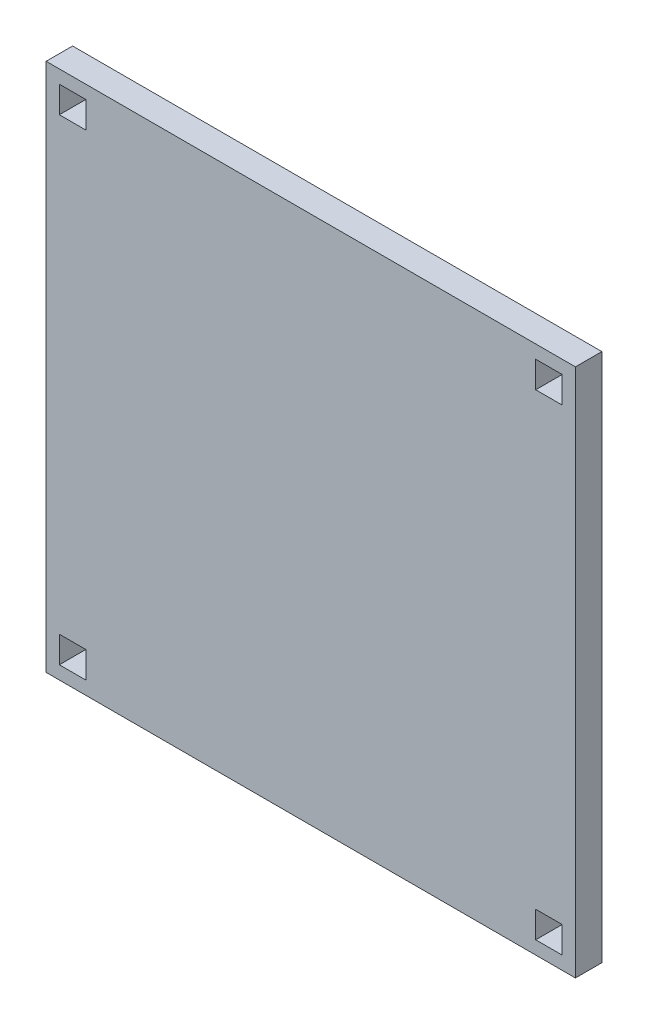
SolidWorks part; units mm, degrees
ref_plane "前视基准面" through (0, 0, 0) normal (0, 0, 1) x (1, 0, 0)
ref_plane "上视基准面" through (0, 0, 0) normal (0, 1, 0) x (1, 0, 0)
ref_plane "右视基准面" through (0, 0, 0) normal (1, 0, 0) x (0, 0, -1)
other "Configuration Table"
sketch "草图1" plane through (0, 0, 0) normal (0, 0, 1) x (1, 0, 0)
  line L1 (-500, -500) -> (500, -500)
  line L2 (-500, -500) -> (-500, 500)
  line L3 (-500, 500) -> (500, 500)
  line L4 (500, -500) -> (500, 500)
  line L5 (-500, -500) -> (500, 500) construction
  line L6 (-500, 500) -> (500, -500) construction
  point P0 (0, 0)
extrude "凸台-拉伸1" add sketch "草图1" along normal blind 50
sketch "草图2" plane through (0, 0, 0) normal (0, 0, 1) x (1, 0, 0)
  line L1 (425, 425) -> (475, 425)
  line L2 (425, 425) -> (425, 475)
  line L3 (425, 475) -> (475, 475)
  line L4 (475, 425) -> (475, 475)
  line L5 (425, 425) -> (475, 475) construction
  line L6 (425, 475) -> (475, 425) construction
  point P0 (450, 450)
extrude "切除-拉伸1" cut sketch "草图2" along normal through all
sketch "草图3" plane through (0, 0, 0) normal (0, 0, 1) x (1, 0, 0)
  line L1 (-475, 425) -> (-425, 425)
  line L2 (-475, 425) -> (-475, 475)
  line L3 (-475, 475) -> (-425, 475)
  line L4 (-425, 425) -> (-425, 475)
  line L5 (-475, 425) -> (-425, 475) construction
  line L6 (-475, 475) -> (-425, 425) construction
  point P0 (-450, 450)
extrude "切除-拉伸2" cut sketch "草图3" along normal through all
sketch "草图4" plane through (0, 0, 0) normal (0, 0, 1) x (1, 0, 0)
  line L1 (425, -475) -> (475, -475)
  line L2 (425, -475) -> (425, -425)
  line L3 (425, -425) -> (475, -425)
  line L4 (475, -475) -> (475, -425)
  line L5 (425, -475) -> (475, -425) construction
  line L6 (425, -425) -> (475, -475) construction
  point P0 (450, -450)
extrude "切除-拉伸3" cut sketch "草图4" along normal through all
sketch "草图5" plane through (0, 0, 0) normal (0, 0, 1) x (1, 0, 0)
  line L1 (-475, -475) -> (-425, -475)
  line L2 (-475, -475) -> (-475, -425)
  line L3 (-475, -425) -> (-425, -425)
  line L4 (-425, -475) -> (-425, -425)
  line L5 (-475, -475) -> (-425, -425) construction
  line L6 (-475, -425) -> (-425, -475) construction
  point P0 (-450, -450)
extrude "切除-拉伸4" cut sketch "草图5" along normal through all
